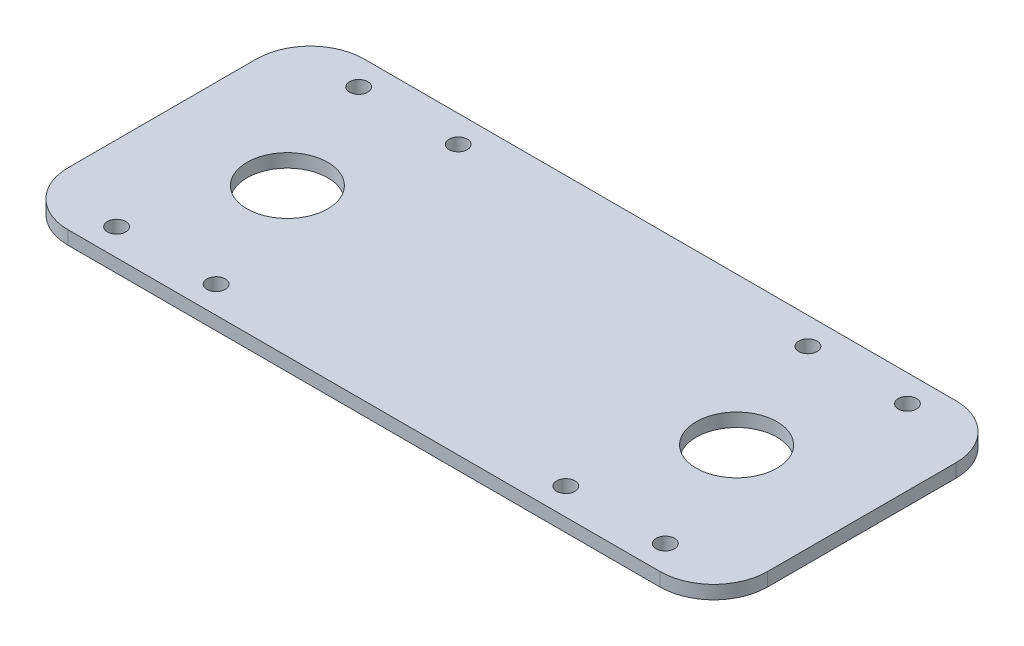
SolidWorks part; units mm, degrees
ref_plane "Front Plane" through (0, 0, 0) normal (0, 0, 1) x (1, 0, 0)
ref_plane "Top Plane" through (0, 0, 0) normal (0, 1, 0) x (1, 0, 0)
ref_plane "Right Plane" through (0, 0, 0) normal (1, 0, 0) x (0, 0, -1)
sketch "Sketch1" plane through (0, 0, 0) normal (0, 1, 0) x (1, 0, 0)
  line L1 (10, 0) -> (120, 0)
  line L2 (0, 10) -> (0, 45)
  line L3 (10, 55) -> (120, 55)
  line L4 (130, 10) -> (130, 45)
  arc A0 (10, 55) -> (0, 45) centre (10, 45) ccw
  arc A1 (0, 10) -> (10, 0) centre (10, 10) ccw
  arc A2 (130, 10) -> (120, 0) centre (120, 10) cw
  arc A3 (120, 55) -> (130, 45) centre (120, 45) cw
  point P7 (0, 55)
  point P10 (0, 0)
  point P13 (130, 0)
  dimension "D3" = 10
  dimension "D4" = 10
  dimension "D5" = 10
  dimension "D6" = 10
  dimension "D1" = 130
  dimension "D2" = 55
extrude "Boss-Extrude1" add sketch "Sketch1" along normal blind 2.5
sketch "Sketch2" plane through (0, 2.5, 0) normal (0, 1, 0) x (1, 0, 0)
  line L0 (0, 45) -> (0, 10) construction
  line L1 (10, 0) -> (120, 0) construction
  line L2 (120, 55) -> (10, 55) construction
  line L3 (65, 55) -> (65, 0) construction
  circle A0 centre (14, 5) radius 1.7
  circle A1 centre (14, 50) radius 1.7
  circle A2 centre (116, 5) radius 1.7
  circle A3 centre (116, 50) radius 1.7
  dimension "D2" = 14
  dimension "D3" = 5
  dimension "D5" = 5
extrude "Cut-Extrude1" cut sketch "Sketch2" against normal through all
sketch "Sketch3" plane through (0, 2.5, 0) normal (0, 1, 0) x (1, 0, 0)
  circle A1 centre (32.5, 50) radius 1.7
  circle A2 centre (32.5, 5) radius 1.7
  circle A3 centre (97.5, 5) radius 1.7
  circle A4 centre (97.5, 50) radius 1.7
extrude "Cut-Extrude2" cut sketch "Sketch3" against normal blind 10
sketch "Sketch4" plane through (0, 2.5, 0) normal (0, 1, 0) x (1, 0, 0)
  line L0 (65, 55) -> (65, 0) construction
  line L1 (120, 55) -> (10, 55) construction
  line L2 (10, 0) -> (120, 0) construction
  circle A0 centre (23.25, 27.5) radius 7.5
  circle A1 centre (106.75, 27.5) radius 7.5
extrude "Cut-Extrude3" cut sketch "Sketch4" against normal blind 10
